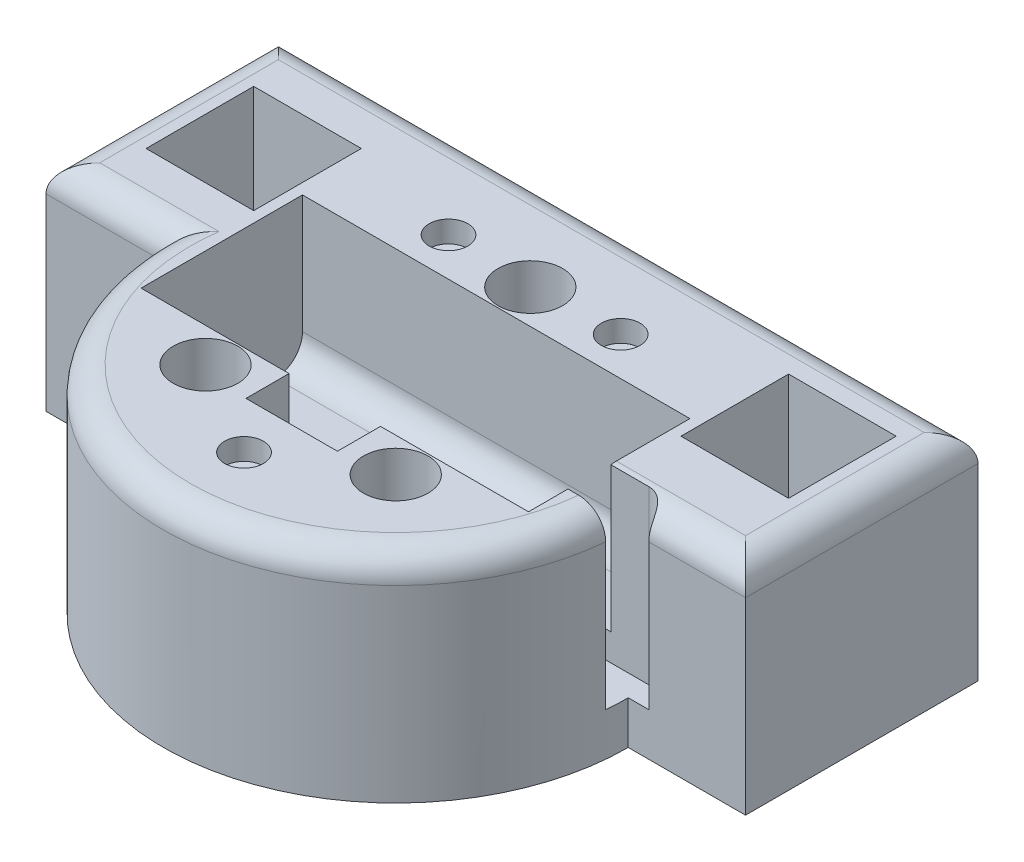
SolidWorks part; units mm, degrees
ref_plane "Front Plane" through (0, 0, 0) normal (0, 0, 1) x (1, 0, 0)
ref_plane "Top Plane" through (0, 0, 0) normal (0, 1, 0) x (1, 0, 0)
ref_plane "Right Plane" through (0, 0, 0) normal (1, 0, 0) x (0, 0, -1)
sketch "Sketch1" plane through (0, 0, 0) normal (0, 1, 0) x (1, 0, 0)
  line L0 (-65, 43.2) -> (65, 43.2)
  line L1 (43.2, 0) -> (65, 0)
  line L2 (65, 0) -> (65, 43.2)
  line L3 (-43.2, 0) -> (-65, 0)
  line L4 (-65, 0) -> (-65, 43.2)
  circle A0 centre (0, 0) radius 25 construction
  circle A1 centre (0, 0) radius 43.2
  point P6 (0, 43.2)
  dimension "D1" = 86.4
  dimension "D2" = 50
  dimension "D3" = 130
extrude "Boss-Extrude1" add sketch "Sketch1" along normal blind 40 contours A1 | A1 L0 L4 L3 | A1 L1 L2 L0
sketch "Sketch2" plane through (0, 40, 0) normal (0, 1, 0) x (1, 0, 0)
  line L0 (65, 25) -> (48, 25) construction
  line L1 (65, 0) -> (65, 43.2) construction
  line L2 (48, 25) -> (48, 43.2) construction
  line L3 (-65, 43.2) -> (65, 43.2) construction
  line L4 (-65, 21.6) -> (-48, 21.6) construction
  line L5 (-65, 0) -> (-65, 43.2) construction
  line L6 (-48, 21.6) -> (-48, 43.2) construction
  line L8 (38, 15) -> (58, 15)
  line L9 (38, 15) -> (38, 35)
  line L10 (38, 35) -> (58, 35)
  line L11 (58, 15) -> (58, 35)
  line L12 (38, 15) -> (58, 35) construction
  line L13 (38, 35) -> (58, 15) construction
  line L14 (-58, 11.6) -> (-38, 11.6)
  line L15 (-58, 11.6) -> (-58, 31.6)
  line L16 (-58, 31.6) -> (-38, 31.6)
  line L17 (-38, 11.6) -> (-38, 31.6)
  line L18 (-58, 11.6) -> (-38, 31.6) construction
  line L19 (-58, 31.6) -> (-38, 11.6) construction
  circle A0 centre (0, 0) radius 25 construction
  circle A1 centre (0, 25) radius 3
  circle A10 centre (0, 0) radius 25 construction
  circle A12 centre (0, 0) radius 25 construction
  circle A13 centre (17.6777, -17.6777) radius 3
  circle A14 centre (0, 0) radius 25 construction
  circle A16 centre (0, 0) radius 25 construction
  circle A17 centre (-17.6777, -17.6777) radius 3
  circle A18 centre (0, 0) radius 25 construction
  circle A20 centre (0, 0) radius 25 construction
  circle A22 centre (0, 0) radius 25 construction
  arc A23 (2.9946, -24.82) -> (-2.9946, -24.82) centre (0, -25) ccw [skipped]
  arc A24 (24.82, -2.9946) -> (24.82, 2.9946) centre (25, 0) ccw [skipped]
  arc A25 (-24.82, 2.9946) -> (-24.82, -2.9946) centre (-25, 0) ccw [skipped]
  arc A26 (-19.6679, 15.4329) -> (-15.4329, 19.6679) centre (-17.6777, 17.6777) ccw [skipped]
  arc A27 (19.6679, 15.4329) -> (15.4329, 19.6679) centre (17.6777, 17.6777) ccw [skipped]
  point P21 (0, -12.5)
  point P30 (0, 0)
  dimension "D1" = 8
  dimension "D2" = 50
  dimension "D3" = 6
  dimension "D4" = 17
  dimension "D5" = 20
  dimension "D6" = 20
extrude "Cut-Extrude1" cut sketch "Sketch2" against normal blind 50
sketch "Sketch3" plane through (0, 40, 0) normal (0, 1, 0) x (1, 0, 0)
  line L0 (0, -11.3388) -> (0, -19.3388)
  line L1 (-36, -11.3388) -> (36, -11.3388)
  line L2 (-36, -11.3388) -> (-36, 18.6612)
  line L3 (-36, 18.6612) -> (36, 18.6612)
  line L4 (36, -11.3388) -> (36, 18.6612)
  line L5 (-36, 3.6612) -> (36, 3.6612) construction
  line L6 (0, 3.6612) -> (0, -43.2) construction
  line L7 (0, -19.3388) -> (8.5, -19.3388)
  line L8 (8.5, -19.3388) -> (8.5, -11.3388)
  line L9 (0, -19.3388) -> (-8.5, -19.3388)
  line L10 (-8.5, -19.3388) -> (-8.5, -11.3388)
  line L11 (0, 25) -> (0, 18.6612) construction
  line L12 (17.6777, -17.6777) -> (17.6777, -11.3388) construction
  circle A1 centre (0, 0) radius 43.2 construction
  dimension "D1" = 8
  dimension "D2" = 8.5
  dimension "D3" = 72
  dimension "D4" = 30
  dimension "D5" = 6.3388
extrude "Cut-Extrude2" cut sketch "Sketch3" against normal blind 27 contours L7 L8 L1 L0 | L10 L9 L0 L1 | L1 L4 L3 L2
fillet "Fillet1" radius 5 3 edges at (0, 13, -18.6612) (22.25, 13, 11.3388) (-22.25, 13, 11.3388)
sketch "Sketch4" plane through (0, 40, 0) normal (0, 1, 0) x (1, 0, 0)
  line L3 (23.0144, 4) -> (43.0144, 4)
  line L4 (23.0144, -4) -> (43.0144, -4)
  circle A1 centre (23.0144, 0) radius 4
  circle A2 centre (0, 0) radius 43.2 construction
  arc A3 (43.0144, 4) -> (43.0144, -4) centre (43.0144, 0) cw
  dimension "D1" = 8
  dimension "D2" = 20
extrude "Cut-Extrude3" cut sketch "Sketch4" against normal blind 32
sketch "Sketch5" plane through (0, 40, 0) normal (0, 1, 0) x (1, 0, 0)
  line L0 (-36, -12.2) -> (-36, -20.2) construction
  line L1 (-36, -20.2) -> (36, -20.2) construction
  line L2 (36, -20.2) -> (36, -12.2) construction
  line L3 (-36, -12.2) -> (36, -12.2) construction
  line L4 (-36, 17.8) -> (-36, 25.8) construction
  line L5 (-36, 25.8) -> (36, 25.8) construction
  line L6 (36, 25.8) -> (36, 17.8) construction
  line L7 (36, 17.8) -> (-36, 17.8) construction
  line L8 (-16, 25.8) -> (-16, 17.8) construction
  line L9 (16, 25.8) -> (16, 17.8) construction
  line L10 (-16, -12.2) -> (-16, -20.2) construction
  line L11 (16, -12.2) -> (16, -20.2) construction
  line L12 (36, 17.8) -> (36, -12.2) construction
  line L13 (0, -12.2) -> (0, -43.2) construction
  line L14 (-8.5, -28.2) -> (8.5, -28.2) construction
  circle A2 centre (16, 25.8) radius 3.6
  circle A3 centre (-16, 25.8) radius 3.6
  arc A4 (43.0144, 4) -> (43.0144, -4) centre (0, 0) ccw construction
  circle A5 centre (0, -28.2) radius 3.6
  dimension "D7" = 7.2
  dimension "D8" = 8
  dimension "D1" = 8
  dimension "D2" = 8
  dimension "D3" = 20
  dimension "D4" = 20
  dimension "D5" = 20
  dimension "D6" = 20
extrude "Cut-Extrude4" cut sketch "Sketch5" against normal blind 4
fillet "Fillet3" radius 5 6 edges at (-2.0022, 40, 43.1536) (56.0072, 40, 0) (-54.1, 40, 0) (-65, 40, -21.6) (65, 40, -21.6) (0, 40, -43.2)
sketch "Sketch7" plane through (0, 40, 0) normal (0, 1, 0) x (1, 0, 0)
  line L0 (-36, 18.6612) -> (36, 18.6612) construction
  line L1 (8.5, -11.3388) -> (36, -11.3388) construction
  circle A0 centre (0, 25) radius 6
  circle A1 centre (17.6777, -17.6777) radius 6
  circle A2 centre (-17.6777, -17.6777) radius 6
  dimension "D1" = 12
  dimension "D2" = 6.3388
  dimension "D3" = 6.3388
extrude "Cut-Extrude5" cut sketch "Sketch7" against normal blind 36 from offset 0
